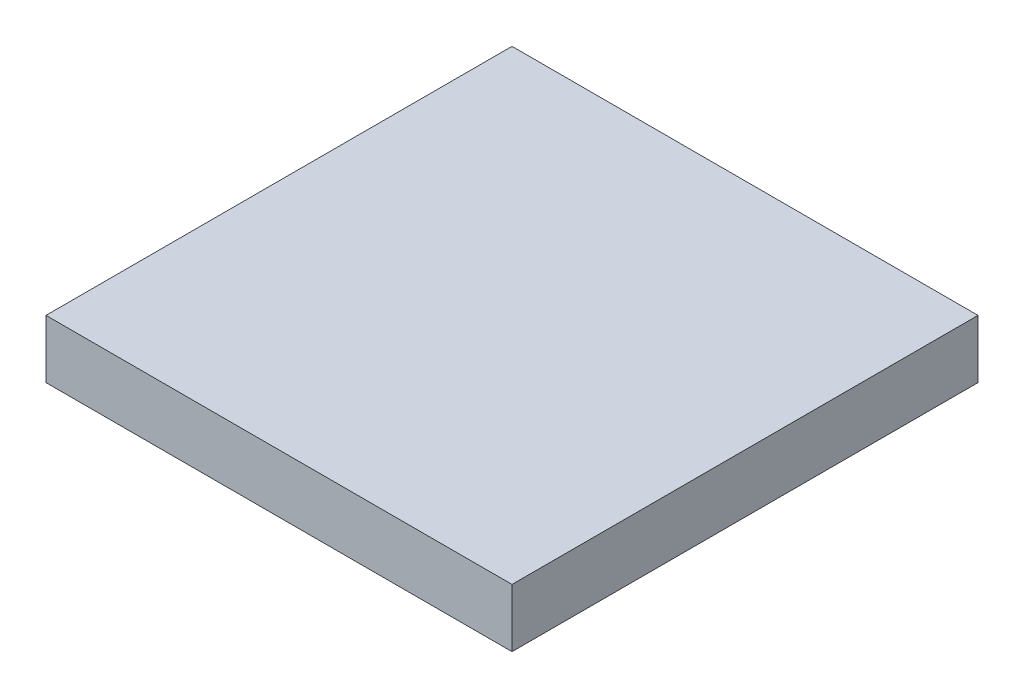
SolidWorks part; units mm, degrees
ref_plane "Front Plane" through (0, 0, 0) normal (0, 0, 1) x (1, 0, 0)
ref_plane "Top Plane" through (0, 0, 0) normal (0, 1, 0) x (1, 0, 0)
ref_plane "Right Plane" through (0, 0, 0) normal (1, 0, 0) x (0, 0, -1)
sketch "Sketch1" plane through (0, 0, 0) normal (0, 1, 0) x (1, 0, 0)
  line L1 (-38.5986, 41.297) -> (63.0014, 41.297)
  line L2 (-38.5986, 41.297) -> (-38.5986, -60.303)
  line L3 (-38.5986, -60.303) -> (63.0014, -60.303)
  line L4 (63.0014, 41.297) -> (63.0014, -60.303)
  dimension "D1" = 101.6
  dimension "D2" = 101.6
extrude "Boss-Extrude1" add sketch "Sketch1" along normal blind 12.7
